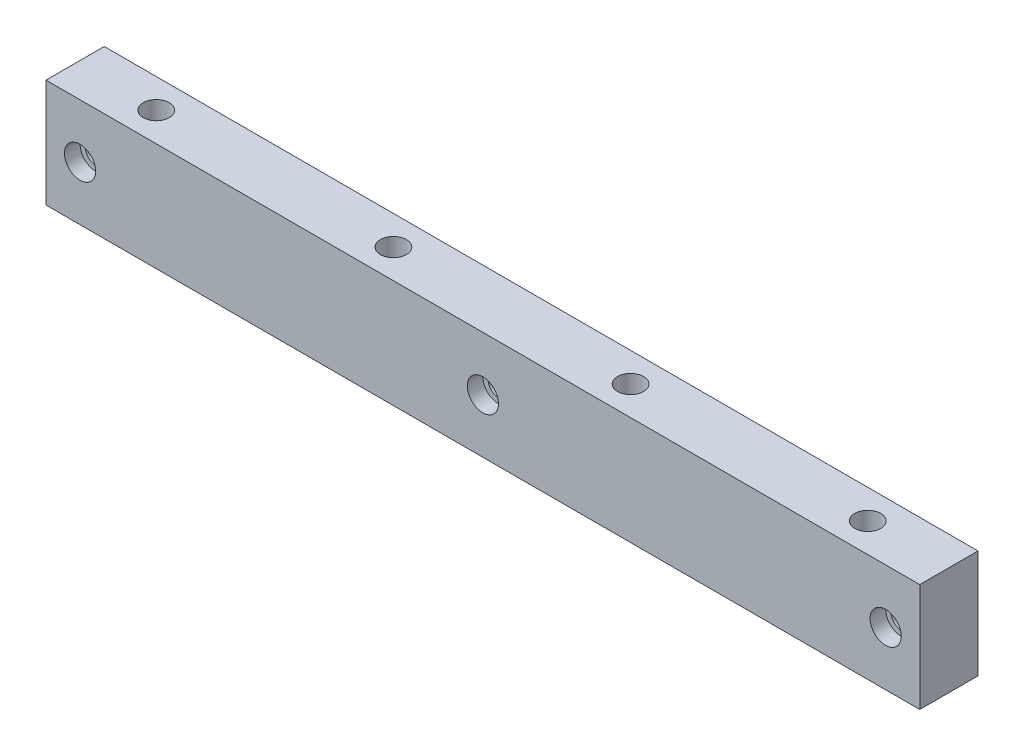
SolidWorks part; units mm, degrees
material "7075-T6 (SN)"
ref_plane "X-Y Datum" through (0, 0, 0) normal (0, 0, 1) x (1, 0, 0)
ref_plane "X-Z Datum" through (0, 0, 0) normal (0, 1, 0) x (1, 0, 0)
ref_plane "Y-Z Datum" through (0, 0, 0) normal (1, 0, 0) x (0, 0, -1)
sketch "Sketch1" plane through (0, 0, 0) normal (0, 1, 0) x (1, 0, 0)
  line L0 (133.35, 8.89) -> (108.585, 8.89) construction
  line L1 (133.35, 17.78) -> (-133.35, 17.78)
  line L2 (133.35, 17.78) -> (133.35, 0)
  line L3 (133.35, 0) -> (-133.35, 0)
  line L4 (-133.35, 17.78) -> (-133.35, 0)
  line L7 (108.585, 8.89) -> (36.195, 8.89) construction
  line L8 (36.195, 8.89) -> (-36.195, 8.89) construction
  line L9 (-36.195, 8.89) -> (-108.585, 8.89) construction
  line L10 (-108.585, 8.89) -> (-133.35, 8.89) construction
  circle A0 centre (108.585, 8.89) radius 3.9688
  circle A1 centre (36.195, 8.89) radius 3.9687
  circle A2 centre (-36.195, 8.89) radius 3.9687
  circle A3 centre (-108.585, 8.89) radius 3.9688
  point P0 (0, 0)
  point P19 (0, 8.89)
  dimension "D3" = 7.9375
  dimension "D1" = 266.7
  dimension "D2" = 17.78
  dimension "D4" = 72.39
  dimension "D5" = 24.765
extrude "Boss-Extrude1" add sketch "Sketch1" against normal blind 33.02
sketch "Sketch2" plane through (0, 0, 0) normal (0, 0, 1) x (1, 0, 0)
  line L0 (112.5537, 0) -> (112.5537, -33.02) construction
  line L1 (-133.35, 0) -> (133.35, 0) construction
  line L2 (-133.35, -33.02) -> (133.35, -33.02) construction
  line L3 (104.6162, 0) -> (104.6162, -33.02) construction
  line L4 (-104.6162, 0) -> (-104.6162, -33.02) construction
  line L5 (-112.5537, 0) -> (-112.5537, -33.02) construction
  line L6 (112.5537, 0) -> (104.6162, 0) construction
  line L7 (112.5537, 0) -> (104.6162, 0) construction
  line L8 (-104.6162, 0) -> (-112.5537, 0) construction
  line L9 (-104.6162, 0) -> (-112.5537, 0) construction
  line L10 (133.35, -16.51) -> (112.5537, -16.51) construction
  line L12 (133.35, -33.02) -> (133.35, 0) construction
  line L13 (-112.5537, -16.51) -> (-133.35, -16.51) construction
  line L14 (-133.35, -33.02) -> (-133.35, 0) construction
  circle A0 centre (122.9519, -16.51) radius 3.175
  circle A1 centre (0, -16.51) radius 3.175
  circle A2 centre (-122.9519, -16.51) radius 3.175
  point P12 (108.585, 0)
  point P15 (-108.585, 0)
  point P33 (-122.9519, -16.51)
  point P34 (122.9519, -16.51)
  dimension "D3" = 6.35
  dimension "D1" = 7.9375
  dimension "D2" = 7.9375
extrude "Cut-Extrude1" cut sketch "Sketch2" against normal up to surface (17.78 mm away) up to face at (0, -16.51, -17.78)
sketch "Sketch3" plane through (0, 0, 0) normal (0, 0, 1) x (1, 0, 0)
  circle A0 centre (122.9519, -16.51) radius 4.7625
  circle A1 centre (0, -16.51) radius 4.7625
  circle A2 centre (-122.9519, -16.51) radius 4.7625
  dimension "D1" = 9.525
extrude "Cut-Extrude2" cut sketch "Sketch3" against normal blind 4.7752
